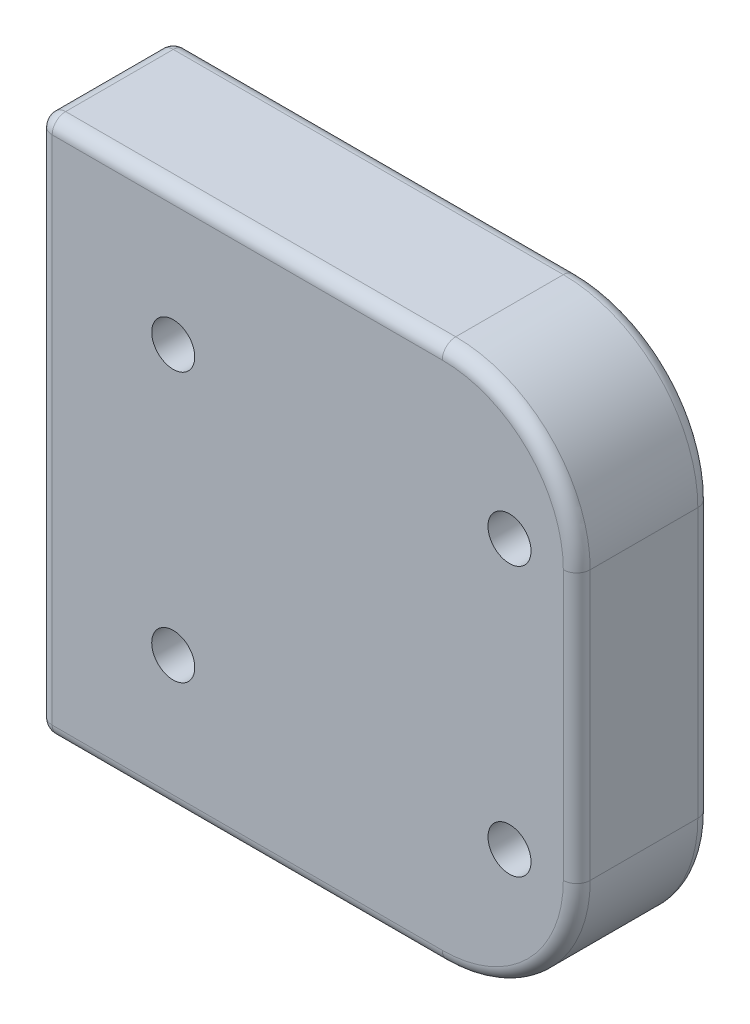
SolidWorks part; units mm, degrees
ref_plane "前视基准面" through (0, 0, 0) normal (0, 0, 1) x (1, 0, 0)
ref_plane "上视基准面" through (0, 0, 0) normal (0, 1, 0) x (1, 0, 0)
ref_plane "右视基准面" through (0, 0, 0) normal (1, 0, 0) x (0, 0, -1)
sketch "草图1" plane through (0, 0, 0) normal (0, 0, 1) x (1, 0, 0)
  line L1 (-20, -20) -> (20, -20) construction
  line L2 (-20, -20) -> (-20, 20)
  line L3 (-20, 20) -> (20, 20) construction
  line L4 (20, -20) -> (20, 20) construction
  line L5 (-20, -20) -> (20, 20) construction
  line L6 (-20, 20) -> (20, -20) construction
  line L7 (-20, 20) -> (20, 20)
  line L8 (-20, -20) -> (20, -20)
  line L9 (20, -20) -> (20, 20)
  point P0 (0, 0)
  dimension "D1" = 40
  dimension "D2" = 40
extrude "凸台-拉伸1" add sketch "草图1" along normal blind 10
sketch "草图2" plane through (0, 0, 10) normal (0, 0, 1) x (1, 0, 0)
  line L0 (0, 0) -> (50000, 0) construction
  line L7 (-10, -10) -> (-10, 10) construction
  line L8 (-10, 10) -> (15, 10) construction
  line L9 (15, -10) -> (15, 10) construction
  line L10 (-10, -10) -> (15, 10) construction
  line L11 (-10, 10) -> (15, -10) construction
  line L12 (2.5, 0) -> (2.5, 50000) construction
  line L13 (-10, -10) -> (15, -10) construction
  circle A4 centre (-10, 10) radius 1.6
  circle A5 centre (15, 10) radius 1.6
  circle A6 centre (15, -10) radius 1.6
  circle A7 centre (-10, -10) radius 1.6
  point P0 (2.5, 0)
  dimension "D3" = 2.5
  dimension "D4" = 3.2
  dimension "D1" = 20
  dimension "D2" = 25
extrude "切除-拉伸1" cut sketch "草图2" against normal through all
fillet "圆角1" radius 10 2 edges at (20, -20, 5) (20, 20, 5)
fillet "圆角2" radius 1 14 edges at (-5, -20, 0) (-5, -20, 10) (-20, 0, 0) (-5, 20, 0) (-5, 20, 10) (-20, 0, 10) (-20, -20, 5) (-20, 20, 5) (17.0711, -17.0711, 0) (20, 0, 0) (17.0711, 17.0711, 0) (17.0711, -17.0711, 10) (20, 0, 10) (17.0711, 17.0711, 10)
equation "\"3。2\"=3.16193"
